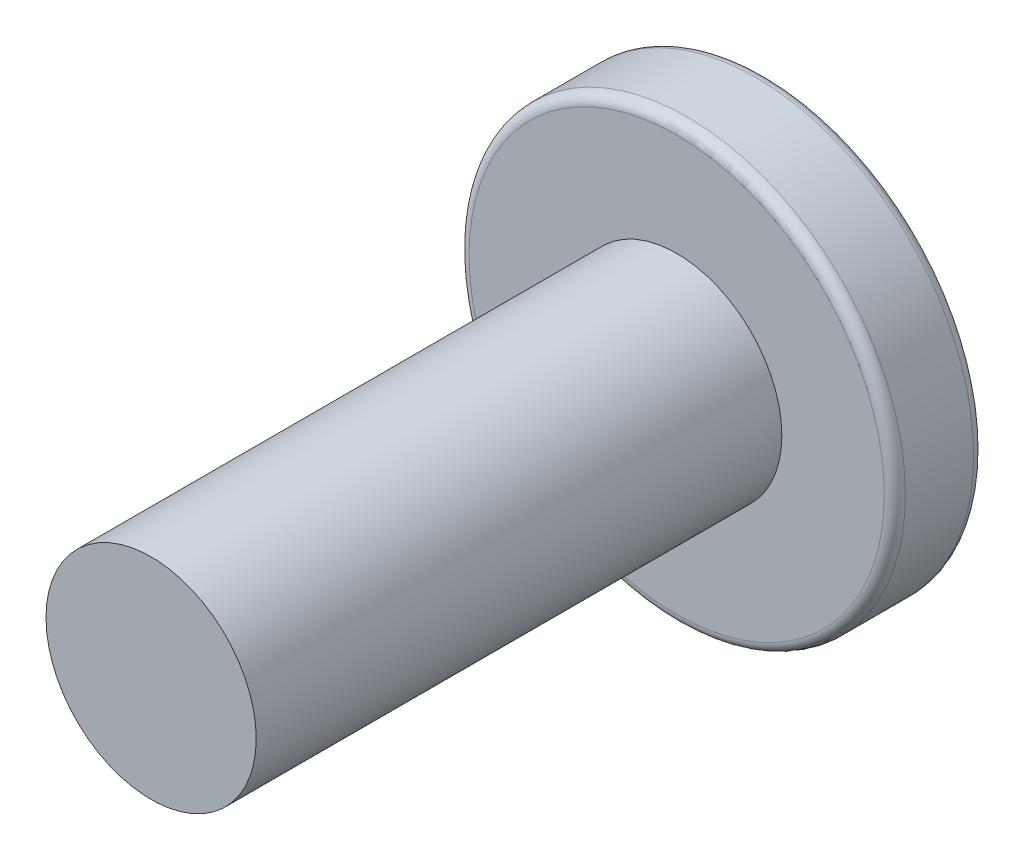
SolidWorks part; units mm, degrees
material "AISI 304"
ref_plane "前视基准面" through (0, 0, 0) normal (0, 0, 1) x (1, 0, 0)
ref_plane "上视基准面" through (0, 0, 0) normal (0, 1, 0) x (1, 0, 0)
ref_plane "右视基准面" through (0, 0, 0) normal (1, 0, 0) x (0, 0, -1)
other "Configuration Table"
sketch "草图1" plane through (0, 0, 0) normal (0, 0, 1) x (1, 0, 0)
  circle A0 centre (0, 0) radius 4.15
  dimension "D1" = 8.3
extrude "凸台-拉伸1" add sketch "草图1" along normal blind 1.7
sketch "草图2" plane through (0, 0, 1.7) normal (0, 0, 1) x (1, 0, 0)
  circle A1 centre (0, 0) radius 2
  dimension "D2" = 4
extrude "凸台-拉伸2" add sketch "草图2" along normal blind 10
fillet "圆角1" radius 0.2 2 edges at (4.15, 0, 0) (4.15, 0, 1.7)
sketch "草图3" plane through (0, 0, 0) normal (0, 0, -1) x (-1, 0, 0)
  line L0 (0, 0) -> (1.1547, 0) construction
  line L1 (1.1547, 0) -> (0.5774, 1)
  line L2 (0.5774, 1) -> (-0.5774, 1)
  line L3 (-0.5774, 1) -> (-1.1547, 0)
  line L4 (-1.1547, 0) -> (-0.5774, -1)
  line L5 (-0.5774, -1) -> (0.5774, -1)
  line L6 (0.5774, -1) -> (1.1547, 0)
  circle A0 centre (0, 0) radius 1 construction
  dimension "D1" = 2
extrude "切除-拉伸1" cut sketch "草图3" against normal blind 1.5
